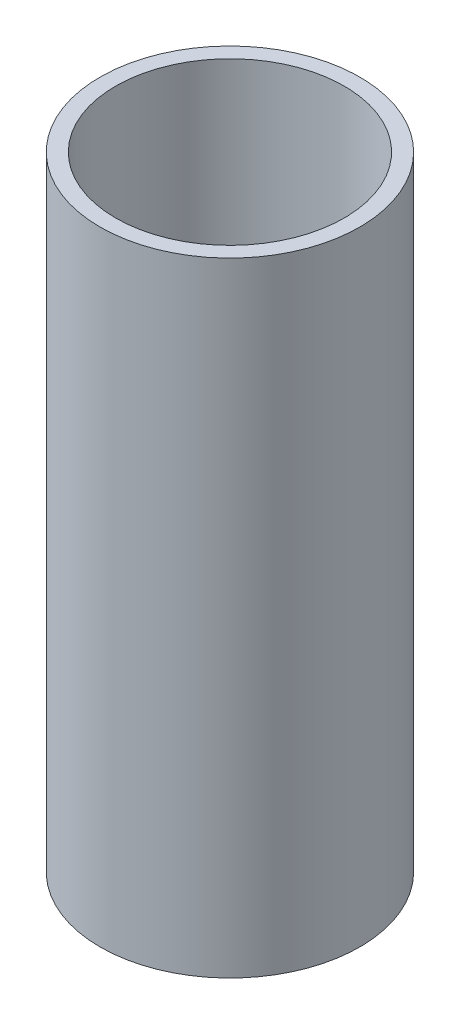
SolidWorks part; units mm, degrees
ref_plane "정면" through (0, 0, 0) normal (0, 0, 1) x (1, 0, 0)
ref_plane "윗면" through (0, 0, 0) normal (0, 1, 0) x (1, 0, 0)
ref_plane "우측면" through (0, 0, 0) normal (1, 0, 0) x (0, 0, -1)
sketch "스케치1" plane through (0, 0, 0) normal (0, 1, 0) x (1, 0, 0)
  circle A0 centre (0, 0) radius 25
  circle A1 centre (0, 0) radius 22
  dimension "D1" = 50
  dimension "D2" = 3
extrude "보스-돌출1" add sketch "스케치1" along normal blind 120
